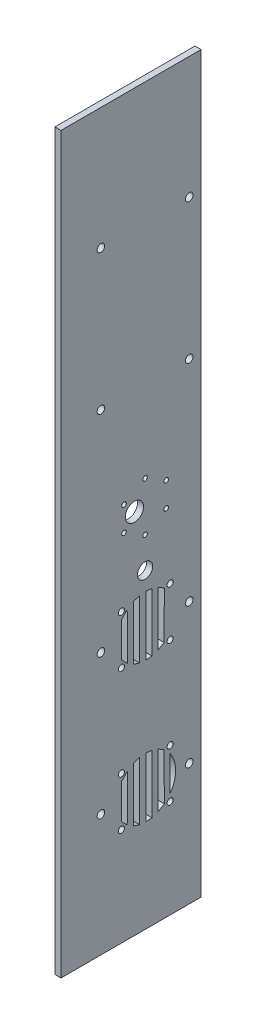
SolidWorks part; units mm, degrees
ref_plane "Alzado" through (0, 0, 0) normal (0, 0, 1) x (1, 0, 0)
ref_plane "Planta" through (0, 0, 0) normal (0, 1, 0) x (1, 0, 0)
ref_plane "Vista lateral" through (0, 0, 0) normal (1, 0, 0) x (0, 0, -1)
sketch "Croquis3" plane through (-90.5016, 0, 0) normal (-1, 0, 0) x (0, 0, 1)
  line L0 (-67.6822, 795.4218) -> (-67.6822, 772.8149)
  line L1 (-88, 703.6284) -> (4, 703.6284)
  line L2 (-88, 703.6284) -> (-88, 1185.6284)
  line L3 (-88, 1185.6284) -> (4, 1185.6284)
  line L4 (4, 703.6284) -> (4, 1185.6284)
  line L5 (-59.6822, 802.0004) -> (-59.6822, 766.2363)
  line L6 (-59.6822, 766.2363) -> (-63.8657, 768.7778)
  line L7 (-63.8657, 768.7778) -> (-63.6822, 799.6028)
  line L8 (-63.6822, 799.6028) -> (-59.6822, 802.0004)
  line L9 (-55.6822, 803.2956) -> (-55.6822, 764.941)
  line L10 (-55.6822, 764.941) -> (-51.6822, 764.5283)
  line L11 (-51.6822, 764.5283) -> (-51.6822, 803.7083)
  line L12 (-51.6822, 803.7083) -> (-55.6822, 803.2956)
  line L13 (-47.6822, 803.2956) -> (-47.6822, 764.941)
  line L14 (-47.6822, 764.941) -> (-43.6822, 766.2363)
  line L15 (-43.6822, 766.2363) -> (-43.6822, 802.0004)
  line L16 (-43.6822, 802.0004) -> (-47.6822, 803.2956)
  line L17 (-39.6822, 799.6028) -> (-39.4987, 768.7778)
  line L18 (-39.4987, 768.7778) -> (-35.6822, 772.8149)
  line L19 (-35.6822, 772.8149) -> (-35.6822, 795.4218)
  line L20 (-35.6822, 795.4218) -> (-39.6822, 799.6028)
  line L21 (-35.6822, 887.4218) -> (-39.4987, 891.4588)
  line L22 (-39.4987, 891.4588) -> (-39.6822, 860.6339)
  line L24 (-39.6822, 860.6339) -> (-35.6822, 864.8149)
  line L25 (-35.6822, 864.8149) -> (-35.6822, 887.4218)
  line L26 (-43.6822, 894.0004) -> (-47.6822, 895.2956)
  line L27 (-47.6822, 895.2956) -> (-47.6822, 856.941)
  line L28 (-47.6822, 856.941) -> (-43.6822, 858.2363)
  line L29 (-43.6822, 858.2363) -> (-43.6822, 894.0004)
  line L30 (-51.6822, 895.7083) -> (-55.6822, 895.2956)
  line L31 (-55.6822, 895.2956) -> (-55.6822, 856.941)
  line L32 (-55.6822, 856.941) -> (-51.6822, 856.5283)
  line L33 (-51.6822, 856.5283) -> (-51.6822, 895.7083)
  line L34 (-59.6822, 894.0004) -> (-63.8657, 891.4588)
  line L35 (-63.8657, 891.4588) -> (-63.6822, 860.6339)
  line L36 (-63.6822, 860.6339) -> (-59.6822, 858.2363)
  line L37 (-59.6822, 858.2363) -> (-59.6822, 894.0004)
  circle A0 centre (-80.2238, 783.6284) radius 2.5
  circle A1 centre (-67.6822, 768.1183) radius 2
  circle A2 centre (-67.6822, 800.1183) radius 2
  circle A3 centre (-35.6822, 800.1183) radius 2
  circle A4 centre (-35.6822, 768.1183) radius 2
  circle A5 centre (-22.2238, 783.6284) radius 2.5
  circle A6 centre (-67.6822, 860.1183) radius 2
  circle A7 centre (-67.6822, 892.1183) radius 2
  circle A8 centre (-35.6822, 892.1183) radius 2
  circle A9 centre (-35.6822, 860.1183) radius 2
  circle A10 centre (-22.2238, 875.6284) radius 2.5
  circle A11 centre (-51.2238, 907.7284) radius 5
  circle A12 centre (-51.2238, 928.1128) radius 1.5
  circle A13 centre (-44.2238, 944.6284) radius 6
  circle A14 centre (-37.3606, 936.1167) radius 1.5
  circle A15 centre (-37.3606, 952.1245) radius 1.5
  circle A16 centre (-51.2238, 960.1284) radius 1.5
  circle A17 centre (-65.0869, 952.1245) radius 1.5
  circle A18 centre (-65.0869, 936.1167) radius 1.5
  circle A19 centre (-80.2238, 1013.6284) radius 2.5
  circle A20 centre (-22.2238, 1013.6284) radius 2.5
  circle A21 centre (-22.2238, 1105.6284) radius 2.5
  circle A22 centre (-80.2238, 1105.6284) radius 2.5
  circle A23 centre (-80.2238, 875.6284) radius 2.5
  arc A24 (-67.6822, 772.8149) -> (-67.6822, 795.4218) centre (-51.6822, 784.1183) cw
extrude "Saliente-Extruir1" add sketch "Croquis3" along normal blind 4
